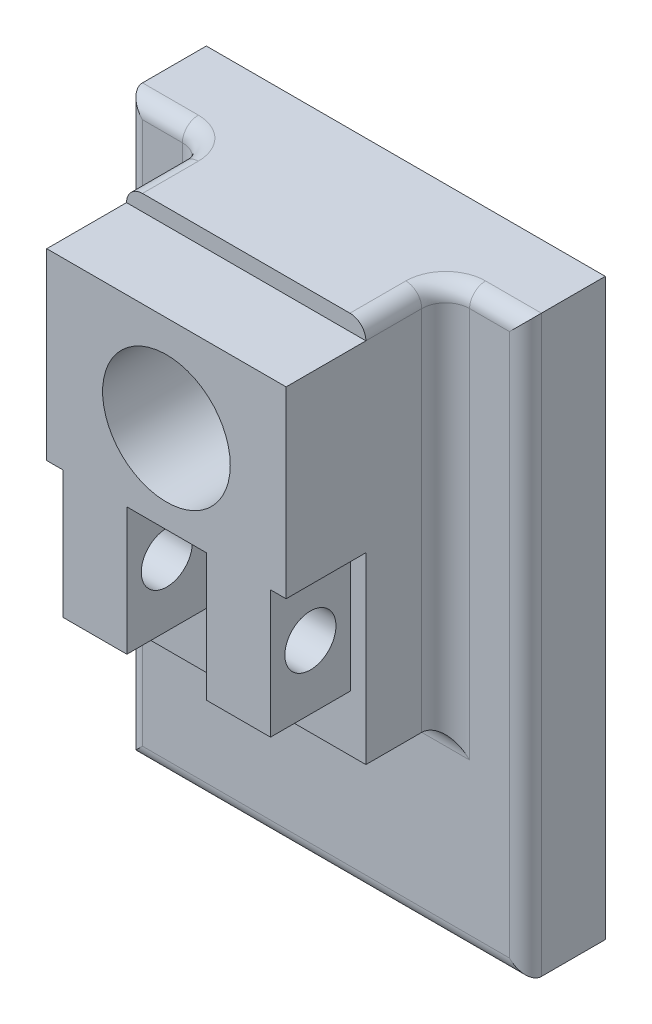
SolidWorks part; units mm, degrees
ref_plane "Front" through (0, 0, 0) normal (0, 0, 1) x (1, 0, 0)
ref_plane "Top" through (0, 0, 0) normal (0, 1, 0) x (1, 0, 0)
ref_plane "Right" through (0, 0, 0) normal (1, 0, 0) x (0, 0, -1)
sketch "Sketch1" plane through (0, 0, 0) normal (0, 0, 1) x (1, 0, 0)
  line L0 (-7.7947, 102.7128) -> (-7.7947, -77.2872) construction
  line L1 (-70.2947, 102.7128) -> (54.7053, 102.7128)
  line L2 (-70.2947, 102.7128) -> (-70.2947, -77.2872)
  line L3 (-70.2947, -77.2872) -> (54.7053, -77.2872)
  line L4 (54.7053, 102.7128) -> (54.7053, -77.2872)
  dimension "D1" = 180
  dimension "D2" = 125
extrude "Base-Extrude" add sketch "Sketch1" along normal blind 25
sketch "Sketch2" plane through (0, 0, 25) normal (0, 0, 1) x (1, 0, 0)
  line L0 (54.7053, 102.7128) -> (-70.2947, 102.7128) construction
  line L1 (-45.2947, 102.7128) -> (29.7053, 102.7128)
  line L2 (-45.2947, 102.7128) -> (-45.2947, -17.2872)
  line L3 (-45.2947, -17.2872) -> (29.7053, -17.2872)
  line L6 (29.7053, 102.7128) -> (29.7053, -17.2872)
  dimension "D1" = 25
  dimension "D2" = 25
  dimension "D3" = 120
extrude "Boss-Extrude1" add sketch "Sketch2" along normal blind 25
fillet "Fillet2" radius 7.5 3 edges at (-45.2947, 42.7128, 25) (-7.7947, -17.2872, 25) (29.7053, 42.7128, 25)
fillet "Fillet4" radius 5 9 edges at (54.7053, 12.7128, 25) (45.9553, 102.7128, 25) (-45.2947, 102.7128, 41.25) (29.7053, 102.7128, 41.25) (-61.5447, 102.7128, 25) (31.902, 102.7128, 27.1967) (-47.4914, 102.7128, 27.1967) (-70.2947, 12.7128, 25) (-7.7947, -77.2872, 25)
sketch "Sketch4" plane through (0, 0, 50) normal (0, 0, 1) x (1, 0, 0)
  line L0 (29.7053, -17.2872) -> (29.7053, 97.7128) construction
  line L1 (-45.2947, 97.7128) -> (-45.2947, -17.2872) construction
  line L3 (29.7053, 40.2128) -> (-45.2947, 40.2128)
  line L4 (29.7053, 40.2128) -> (29.7053, 97.7128)
  line L5 (29.7053, 97.7128) -> (-45.2947, 97.7128)
  line L6 (-45.2947, 40.2128) -> (-45.2947, 97.7128)
extrude "Boss-Extrude2" add sketch "Sketch4" along normal blind 25
sketch "Sketch5" [suppressed] plane through (0, 0, 50) normal (0, 0, 1) x (1, 0, 0)
  line L0 (-45.2947, 40.2128) -> (29.7053, 40.2128) construction
  line L1 (-32.7947, 40.2128) -> (-20.2947, 40.2128)
  line L2 (-32.7947, 40.2128) -> (-32.7947, 0.2128)
  line L3 (-32.7947, 0.2128) -> (-20.2947, 0.2128)
  line L4 (17.2053, 40.2128) -> (17.2053, 0.2128)
  line L5 (-45.2947, 40.2128) -> (-45.2947, -17.2872) construction
  line L6 (29.7053, -17.2872) -> (29.7053, 40.2128) construction
  line L7 (4.7053, 40.2128) -> (17.2053, 40.2128)
  line L8 (-45.2947, 40.2128) -> (29.7053, 40.2128) construction
  line L9 (-20.2947, 40.2128) -> (-20.2947, 0.2128)
  line L11 (4.7053, 40.2128) -> (4.7053, 0.2128)
  line L12 (4.7053, 0.2128) -> (17.2053, 0.2128)
  dimension "D1" = 12.5
  dimension "D2" = 12.5
  dimension "D3" = 12.5
  dimension "D4" = 12.5
  dimension "D5" = 40
extrude "Boss-Extrude3" [suppressed] add sketch "Sketch5" along normal up to vertex
sketch "Sketch6" [suppressed] plane through (-32.7947, 0, 0) normal (-1, 0, 0) x (0, 0, 1)
  line L0 (75, 0.2128) -> (50, 0.2128) construction
  line L1 (75, 40.2128) -> (75, 0.2128) construction
  circle A0 centre (62.5, 20.2128) radius 7.5
  dimension "D2" = 15
  dimension "D1" = 12.5
  dimension "D3" = 20
extrude "Cut-Extrude1" [suppressed] cut sketch "Sketch6" against normal blind 60
sketch "Sketch7" plane through (0, 0, 75) normal (0, 0, 1) x (1, 0, 0)
  line L2 (29.7053, 97.7128) -> (-45.2947, 97.7128) construction
  line L5 (54.7053, 102.7128) -> (54.7053, -77.2872) construction
  circle A0 centre (-7.7947, 67.7128) radius 20
  dimension "D3" = 40
  dimension "D1" = 62.5
  dimension "D2" = 30
extrude "Cut-Extrude2" cut sketch "Sketch7" against normal blind 105
fillet "Fillet8" [suppressed] radius 7.62
fillet "Fillet9" [suppressed] radius 2.5
fillet "Fillet10" [suppressed] radius 2.5
sketch "Sketch8" plane through (0, 0, 50) normal (0, 0, 1) x (1, 0, 0)
  line L0 (-40.181, 40.2128) -> (-20.181, 40.2128)
  line L5 (-40.181, 40.2128) -> (-40.181, 0.2128)
  line L6 (4.819, 40.2128) -> (24.819, 40.2128)
  line L7 (4.819, 40.2128) -> (4.819, 0.2128)
  line L8 (4.819, 0.2128) -> (24.819, 0.2128)
  line L9 (24.819, 40.2128) -> (24.819, 0.2128)
  line L10 (-20.181, 40.2128) -> (-20.181, 0.2128)
  line L11 (-40.181, 0.2128) -> (-20.181, 0.2128)
  dimension "D2" = 20
  dimension "D3" = 40
extrude "Boss-Extrude4" add sketch "Sketch8" along normal blind 25
sketch "Sketch9" plane through (24.819, 0, 0) normal (1, 0, 0) x (0, 0, -1)
  line L0 (-75, 40.2128) -> (-50, 0.2128) construction
  circle A0 centre (-62.5, 20.2128) radius 8
  dimension "D1" = 16
extrude "Cut-Extrude3" cut sketch "Sketch9" against normal blind 89
sketch "Sketch10" plane through (0, 0, 50) normal (0, 0, 1) x (1, 0, 0)
  line L0 (-20.181, 40.2128) -> (-20.181, -17.2872)
  line L1 (-45.2947, -17.2872) -> (29.7053, -17.2872) construction
  line L2 (-20.181, -17.2872) -> (4.819, -17.2872)
  line L3 (4.819, -17.2872) -> (4.819, 40.2128)
  line L4 (4.819, 40.2128) -> (-20.181, 40.2128)
extrude "Cut-Extrude4" cut sketch "Sketch10" against normal blind 31
sketch "Sketch11" plane through (4.819, 0, 0) normal (-1, 0, 0) x (0, 0, 1)
  line L0 (62.5, 20.2128) -> (62.5, 40.2128) construction
  line L1 (75, 40.2128) -> (19, 40.2128) construction
sketch "Sketch12" plane through (0, 40.2128, 0) normal (0, -1, 0) x (1, 0, 0)
  line L0 (4.819, 75) -> (4.819, 19) construction
  line L1 (4.819, 62.4238) -> (-20.181, 62.4238)
  line L2 (4.819, 62.4238) -> (4.819, 19)
  line L3 (4.819, 19) -> (-20.181, 19)
  line L4 (-20.181, 62.4238) -> (-20.181, 19)
  line L5 (4.819, 19) -> (-20.181, 19) construction
  line L6 (-20.181, 75) -> (-20.181, 19) construction
extrude "Cut-Extrude6" cut sketch "Sketch12" against normal blind 7
